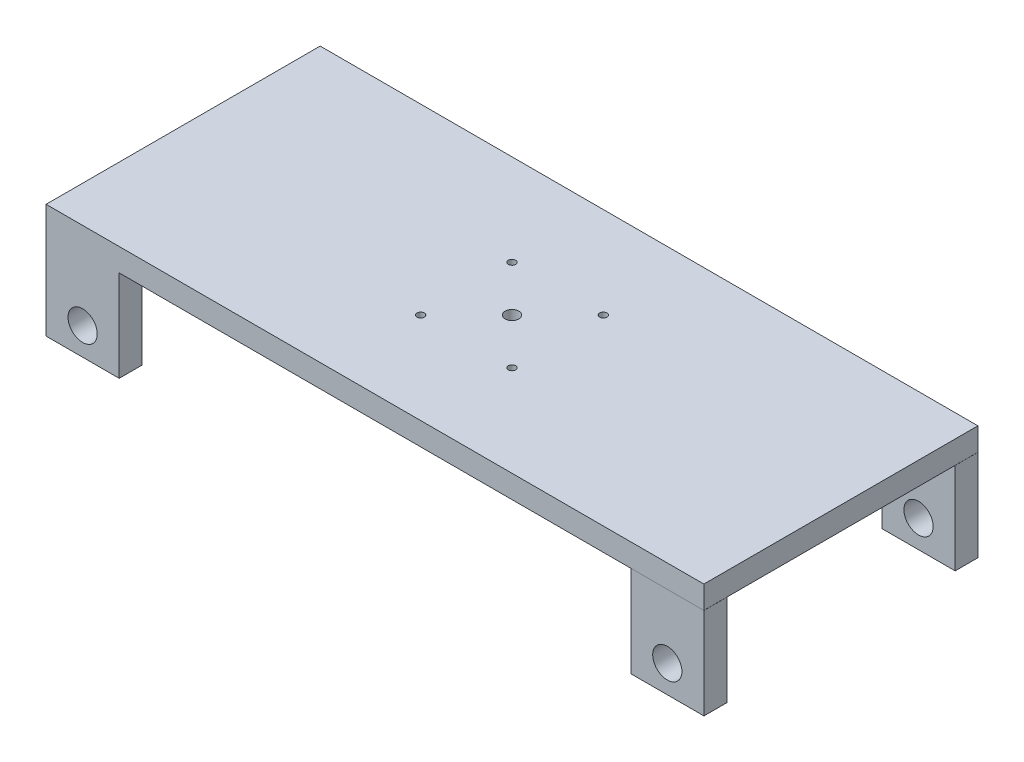
SolidWorks part; units mm, degrees
ref_plane "Front Plane" through (0, 0, 0) normal (0, 0, 1) x (1, 0, 0)
ref_plane "Top Plane" through (0, 0, 0) normal (0, 1, 0) x (1, 0, 0)
ref_plane "Right Plane" through (0, 0, 0) normal (1, 0, 0) x (0, 0, -1)
sketch "Sketch1" plane through (0, 0, 0) normal (0, 1, 0) x (1, 0, 0)
  line L1 (-360, -150) -> (360, -150)
  line L2 (-360, -150) -> (-360, 150)
  line L3 (-360, 150) -> (360, 150)
  line L4 (360, -150) -> (360, 150)
  line L5 (-360, -150) -> (360, 150) construction
  line L6 (-360, 150) -> (360, -150) construction
  point P0 (0, 0)
  dimension "D1" = 300
  dimension "D2" = 720
extrude "Boss-Extrude1" add sketch "Sketch1" along normal blind 25
sketch "Sketch2" plane through (0, 0, 0) normal (0, 1, 0) x (1, 0, 0)
  circle A0 centre (0, 0) radius 7.5
  dimension "D1" = 15
sketch "Sketch3" plane through (0, 0, 0) normal (0, 1, 0) x (1, 0, 0)
  line L1 (-65, 65) -> (65, 65)
  line L2 (-65, 65) -> (-65, -65)
  line L3 (-65, -65) -> (65, -65)
  line L4 (65, 65) -> (65, -65)
  line L5 (-65, 65) -> (65, -65) construction
  line L6 (-65, -65) -> (65, 65) construction
  point P0 (0, 0)
  dimension "D1" = 130
extrude "Boss-Extrude3" add sketch "Sketch3" against normal blind 20 separate body contours L2 L3 L4 L1
extrude "Cut-Extrude7" cut sketch "Sketch2" against normal blind 20 and the other way through all contours A0
ref_plane "Plane1" through (0, -20, 0) normal (0, -1, 0) x (-1, 0, 0)
sketch "Sketch4" plane through (0, -20, 0) normal (0, -1, 0) x (-1, 0, 0)
  line L0 (65, 65) -> (65, -65) construction
  line L1 (65, 65) -> (-65, 65) construction
  circle A0 centre (50, 50) radius 4
  circle A1 centre (50, -50) radius 4
  circle A2 centre (-50, -50) radius 4
  circle A3 centre (-50, 50) radius 4
  point P15 (0, 0)
  dimension "D1" = 8
  dimension "D2" = 15
  dimension "D3" = 15
  dimension "D4" = 4
extrude "Cut-Extrude8" cut sketch "Sketch4" against normal through all
ref_plane "Plane2" through (360, 0, 0) normal (1, 0, 0) x (0, 0, -1)
sketch "Sketch5" plane through (360, 0, 0) normal (1, 0, 0) x (0, 0, -1)
  line L0 (-150, 0) -> (-125, 0)
  line L1 (-150, 0) -> (150, 0) construction
  line L2 (-125, 0) -> (-125, -100)
  line L3 (-125, -100) -> (-150, -100)
  line L4 (-150, -100) -> (-150, 0)
  line L5 (150, 0) -> (125, 0)
  line L6 (125, 0) -> (125, -100)
  line L7 (125, -100) -> (150, -100)
  line L8 (150, -100) -> (150, 0)
  dimension "D1" = 100
  dimension "D2" = 25
extrude "Boss-Extrude4" add sketch "Sketch5" along normal blind 0.1 and the other way blind 80 separate body
ref_plane "Plane5" through (-360, 0, 0) normal (-1, 0, 0) x (0, 0, 1)
sketch "Sketch6" plane through (-360, 0, 0) normal (-1, 0, 0) x (0, 0, 1)
  line L0 (-150, 0) -> (-125, 0)
  line L1 (-125, 0) -> (-125, -100)
  line L2 (-125, -100) -> (-150, -100)
  line L3 (-150, -100) -> (-150, 0)
  line L4 (125, 0) -> (125, -100)
  line L5 (125, -100) -> (150, -100)
  line L6 (150, -100) -> (150, 0)
  line L7 (150, 0) -> (125, 0)
extrude "Boss-Extrude5" add sketch "Sketch6" along normal blind 0.1 and the other way blind 80
ref_plane "Plane6" through (0, 0, 150) normal (0, 0, 1) x (1, 0, 0)
sketch "Sketch7" plane through (0, 0, 150) normal (0, 0, 1) x (1, 0, 0)
  line L0 (280, -100) -> (360.1, -100) construction
  line L1 (360, -89.7669) -> (360, 89.7669) construction
  line L2 (-280, -100) -> (-360.1, -100) construction
  line L3 (-360, 114.2549) -> (-360, -114.2549) construction
  circle A0 centre (320, -70) radius 16
  circle A1 centre (-320, -70) radius 16
  dimension "D1" = 32
  dimension "D3" = 40
  dimension "D5" = 30
  dimension "D2" = 30
  dimension "D6" = 40
  dimension "D4" = 2
extrude "Cut-Extrude9" cut sketch "Sketch7" against normal through all both and the other way through all
